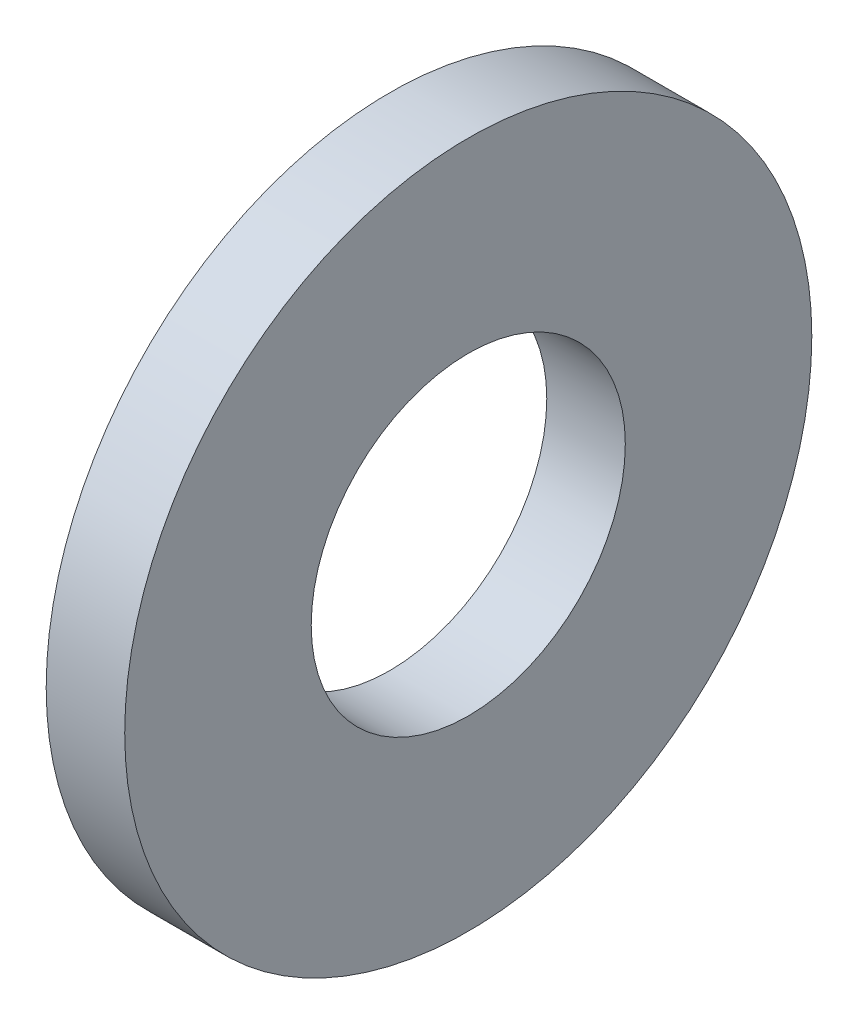
SolidWorks part; units mm, degrees
ref_plane "Plane1" through (0, 0, 0) normal (0, 0, 1) x (1, 0, 0)
ref_plane "Plane2" through (0, 0, 0) normal (0, 1, 0) x (1, 0, 0)
ref_plane "Plane3" through (0, 0, 0) normal (1, 0, 0) x (0, 0, -1)
sketch "Sketch1" plane through (0, 0, 0) normal (1, 0, 0) x (0, 0, -1)
  circle A0 centre (0, 0) radius 1.6
  circle A1 centre (0, 0) radius 3.5
  dimension "Insid_dia" = 3.2
  dimension "OutsideDia" = 7
extrude "Base-Extrude" add sketch "Sketch1" along normal blind 0.8
